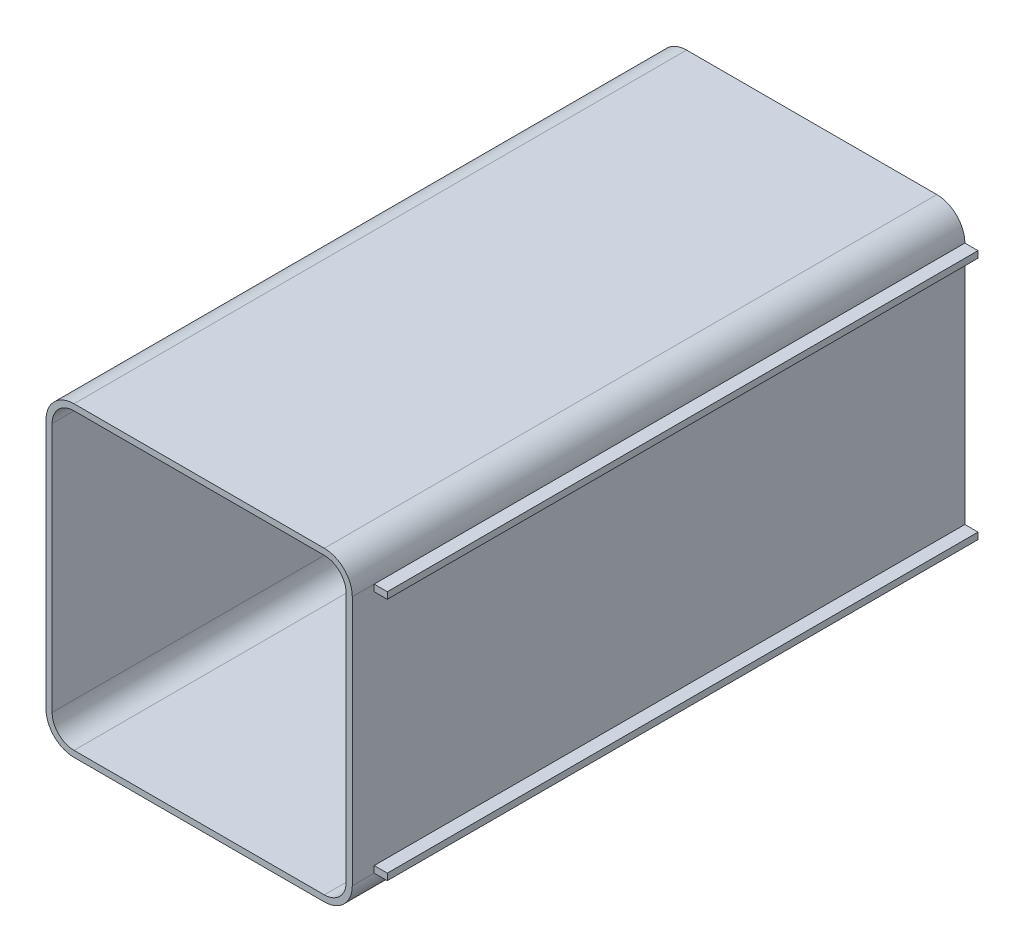
SolidWorks part; units mm, degrees
ref_plane "Front Plane" through (0, 0, 0) normal (0, 0, 1) x (1, 0, 0)
ref_plane "Top Plane" through (0, 0, 0) normal (0, 1, 0) x (1, 0, 0)
ref_plane "Right Plane" through (0, 0, 0) normal (1, 0, 0) x (0, 0, -1)
sketch "Sketch1" plane through (0, 0, 0) normal (0, 0, 1) x (1, 0, 0)
  line L1 (0, 0) -> (70, 0)
  line L2 (0, 0) -> (0, 70)
  line L3 (0, 70) -> (70, 70)
  line L4 (70, 0) -> (70, 70)
  dimension "D1" = 70
  dimension "D2" = 70
extrude "Boss-Extrude1" add sketch "Sketch1" along normal blind 140
sketch "Sketch2" plane through (0, 0, 140) normal (0, 0, 1) x (1, 0, 0)
  line L0 (70, 70) -> (0, 70) construction
  line L1 (1.4, 68.6) -> (68.6, 68.6)
  line L2 (1.4, 68.6) -> (1.4, 1.4)
  line L3 (1.4, 1.4) -> (68.6, 1.4)
  line L4 (68.6, 68.6) -> (68.6, 1.4)
  line L5 (0, 0) -> (70, 0) construction
  line L6 (70, 0) -> (70, 70) construction
  line L7 (0, 70) -> (0, 0) construction
  dimension "D1" = 1.4
  dimension "D2" = 1.4
  dimension "D3" = 1.4
  dimension "D4" = 1.4
extrude "Cut-Extrude1" cut sketch "Sketch2" against normal blind 138.4
fillet "Fillet1" radius 5 4 edges at (68.6, 68.6, 70.8) (68.6, 1.4, 70.8) (1.4, 1.4, 70.8) (1.4, 68.6, 70.8)
fillet "Fillet2" radius 6.4 4 edges at (70, 70, 70) (70, 0, 70) (0, 0, 70) (0, 70, 70)
sketch "Sketch3" plane through (70, 0, 0) normal (1, 0, 0) x (0, 0, -1)
  line L0 (-140, 6.4) -> (0, 6.4) construction
  line L1 (-135, 6.4) -> (0, 6.4)
  line L2 (-135, 6.4) -> (-135, 7.9)
  line L3 (-135, 7.9) -> (0, 7.9)
  line L4 (0, 6.4) -> (0, 7.9)
  line L5 (0, 6.4) -> (0, 63.6) construction
  line L6 (-140, 6.4) -> (-140, 63.6) construction
  line L7 (0, 63.6) -> (-135, 63.6)
  line L8 (0, 63.6) -> (0, 62.1)
  line L9 (0, 62.1) -> (-135, 62.1)
  line L10 (-135, 63.6) -> (-135, 62.1)
  dimension "D1" = 1.5
  dimension "D2" = 1.5
  dimension "D3" = 5
  dimension "D4" = 5
extrude "Boss-Extrude2" add sketch "Sketch3" along normal blind 3
